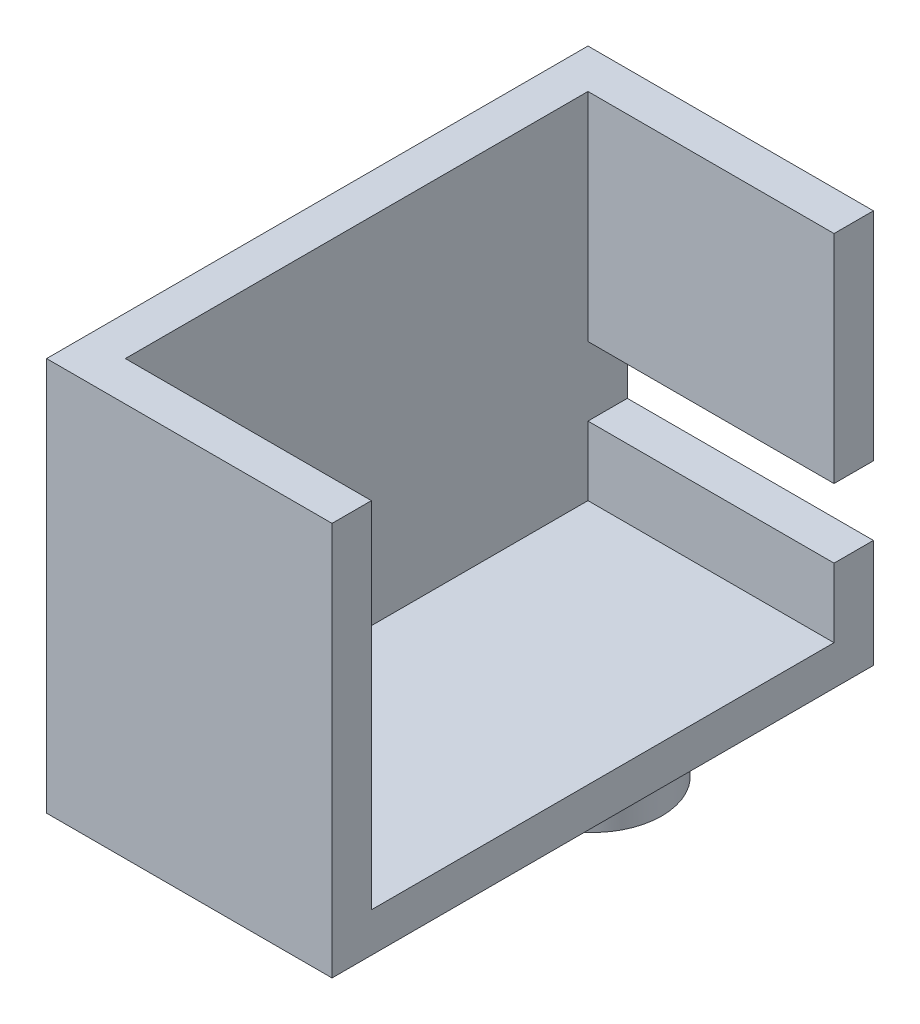
SolidWorks part; units mm, degrees
ref_plane "Спереди" through (0, 0, 0) normal (0, 0, 1) x (1, 0, 0)
ref_plane "Сверху" through (0, 0, 0) normal (0, 1, 0) x (1, 0, 0)
ref_plane "Справа" through (0, 0, 0) normal (1, 0, 0) x (0, 0, -1)
sketch "Эскиз2" plane through (0, 0, 0) normal (1, 0, 0) x (0, 0, -1)
  line L0 (-18.0559, 6.5) -> (18.0559, 6.5) construction
  line L1 (0, 0) -> (-23.5, 0)
  line L2 (0, 0) -> (0, 18)
  line L3 (0, 18) -> (-23.5, 18)
  line L4 (-23.5, 0) -> (-23.5, 18)
  line L5 (-19.1218, 4) -> (19.1218, 4) construction
  point P4 (0, 6.5)
  point P5 (0, 4)
  point P10 (0, 6.5)
  point P11 (6.0015, 6.5)
  point P13 (0, 4)
  point P14 (6.0015, 4)
  point P15 (3.7225, 6.5)
  point P16 (3.7225, 6.5)
  point P17 (6.0015, 4)
  point P19 (6.0015, 6.5)
  dimension "D1" = 23.5
  dimension "D2" = 18
  dimension "D3" = 11.5
  dimension "D4" = 14
extrude "Бобышка-Вытянуть1" add sketch "Эскиз2" along normal blind 12.5
shell "Оболочка7" thickness 2
sketch "Эскиз4" plane through (0, 0, 0) normal (1, 0, 0) x (0, 0, -1)
  line L0 (0, 0) -> (0, 18) construction
  line L1 (0, 0) -> (0, 18) construction
  line L2 (0, 7) -> (0, 3.5)
  line L3 (0, 7) -> (2, 7)
  line L4 (2, 7) -> (2, 3.5)
  line L5 (2, 3.5) -> (0, 3.5)
  line L6 (2, -2) -> (2, 20) construction
  point P0 (0, 7)
  point P4 (0, 3.5)
  dimension "D1" = 11
  dimension "D2" = 14.5
extrude "Вырез-Вытянуть3" cut sketch "Эскиз4" along normal through all
sketch "Эскиз8" plane through (0, 20, 0) normal (0, 1, 0) x (1, 0, 0)
  line L4 (-2, 2) -> (-2, -25.5)
  line L5 (-2, 2) -> (12.5677, 2)
  line L6 (-2, -25.5) -> (12.5677, -25.5)
  line L7 (12.5677, 2) -> (12.5677, -25.5)
extrude "Вырез-Вытянуть5" cut sketch "Эскиз8" against normal blind 2
sketch "Эскиз7" plane through (0, -2, 0) normal (0, -1, 0) x (1, 0, 0)
  line L0 (5.25, -2) -> (5.25, 25.5) construction
  line L1 (12.5, -2) -> (-2, -2) construction
  line L2 (12.5, 25.5) -> (-2, 25.5) construction
  circle A0 centre (5.25, 5) radius 3.5
  dimension "D1" = 7
  dimension "D2" = 7
extrude "Бобышка-Вытянуть2" add sketch "Эскиз7" along normal blind 5
